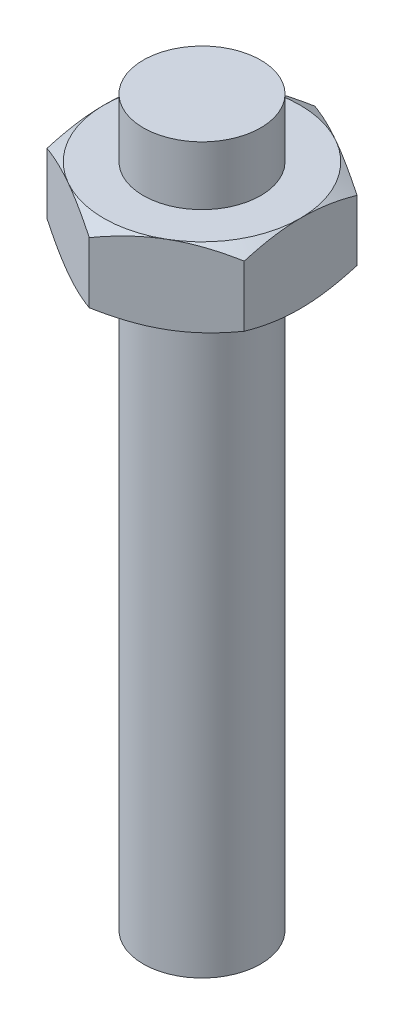
SolidWorks part; units mm, degrees
ref_plane "Front Plane" through (0, 0, 0) normal (0, 0, 1) x (1, 0, 0)
ref_plane "Top Plane" through (0, 0, 0) normal (0, 1, 0) x (1, 0, 0)
ref_plane "Right Plane" through (0, 0, 0) normal (1, 0, 0) x (0, 0, -1)
sketch "Sketch1" plane through (0, 0, 0) normal (0, 1, 0) x (1, 0, 0)
  line L1 (5, 2.9196) -> (-0.0285, 5.79)
  line L2 (-0.0285, 5.79) -> (-5.0285, 2.8703)
  line L3 (-5.0285, 2.8703) -> (-5, -2.9196)
  line L4 (-5, -2.9196) -> (0.0285, -5.79)
  line L5 (0.0285, -5.79) -> (5.0285, -2.8703)
  line L6 (5.0285, -2.8703) -> (5, 2.9196)
extrude "Boss-Extrude1" add sketch "Sketch1" along normal blind 4
sketch "Sketch2" plane through (0, 4, 0) normal (0, 1, 0) x (1, 0, 0)
  circle A0 centre (0, 0) radius 5.0143
extrude "Cut-Extrude1" cut sketch "Sketch2" against normal blind 4 draft 60 flip side to cut
sketch "Sketch3" plane through (0, 0, 0) normal (0, -1, 0) x (1, 0, 0)
  circle A0 centre (0, 0) radius 5.0143
extrude "Cut-Extrude2" cut sketch "Sketch3" against normal blind 4 draft 60 flip side to cut
sketch "Sketch4" plane through (0, 4, 0) normal (0, 1, 0) x (1, 0, 0)
  circle A0 centre (0, 0) radius 3
extrude "Boss-Extrude3" add sketch "Sketch4" along normal blind 3
sketch "Sketch5" plane through (0, 0, 0) normal (0, -1, 0) x (1, 0, 0)
  circle A0 centre (0, 0) radius 3
extrude "Boss-Extrude4" add sketch "Sketch5" along normal blind 30
